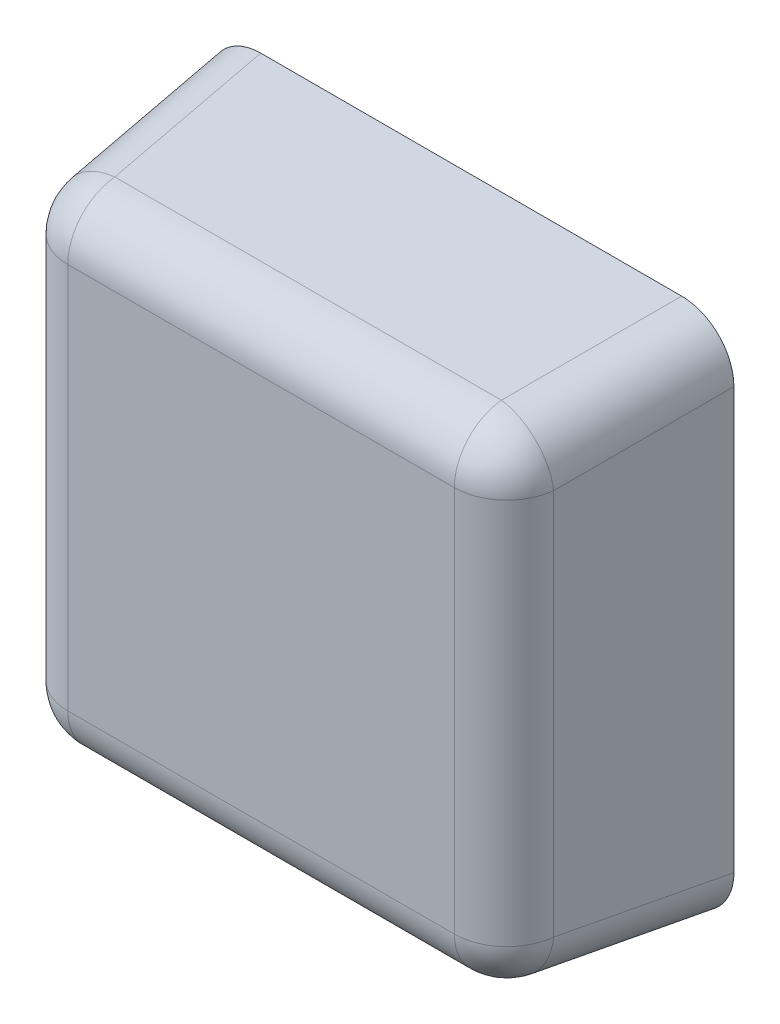
SolidWorks part; units mm, degrees
material "Rubber"
ref_plane "Front Plane" through (0, 0, 0) normal (0, 0, 1) x (1, 0, 0)
ref_plane "Top Plane" through (0, 0, 0) normal (0, 1, 0) x (1, 0, 0)
ref_plane "Right Plane" through (0, 0, 0) normal (1, 0, 0) x (0, 0, -1)
sketch "Sketch1" plane through (0, 0, 0) normal (0, 0, 1) x (1, 0, 0)
  line L1 (0, 0) -> (12.7, 0)
  line L2 (0, 0) -> (0, -12.7)
  line L3 (0, -12.7) -> (12.7, -12.7)
  line L4 (12.7, 0) -> (12.7, -12.7)
  dimension "D1" = 12.7
  dimension "D2" = 12.7
extrude "Boss-Extrude1" add sketch "Sketch1" along normal blind 5.08 draft 6
fillet "Fillet1" radius 1.27 8 edges at (6.35, -0.5339, 5.08) (12.1661, -6.35, 5.08) (6.35, -12.1661, 5.08) (0.5339, -6.35, 5.08) (12.433, -12.433, 2.54) (0.267, -12.433, 2.54) (0.267, -0.267, 2.54) (12.433, -0.267, 2.54)
equation "\"D2@Sketch1\"=\"D1@Sketch1\""
